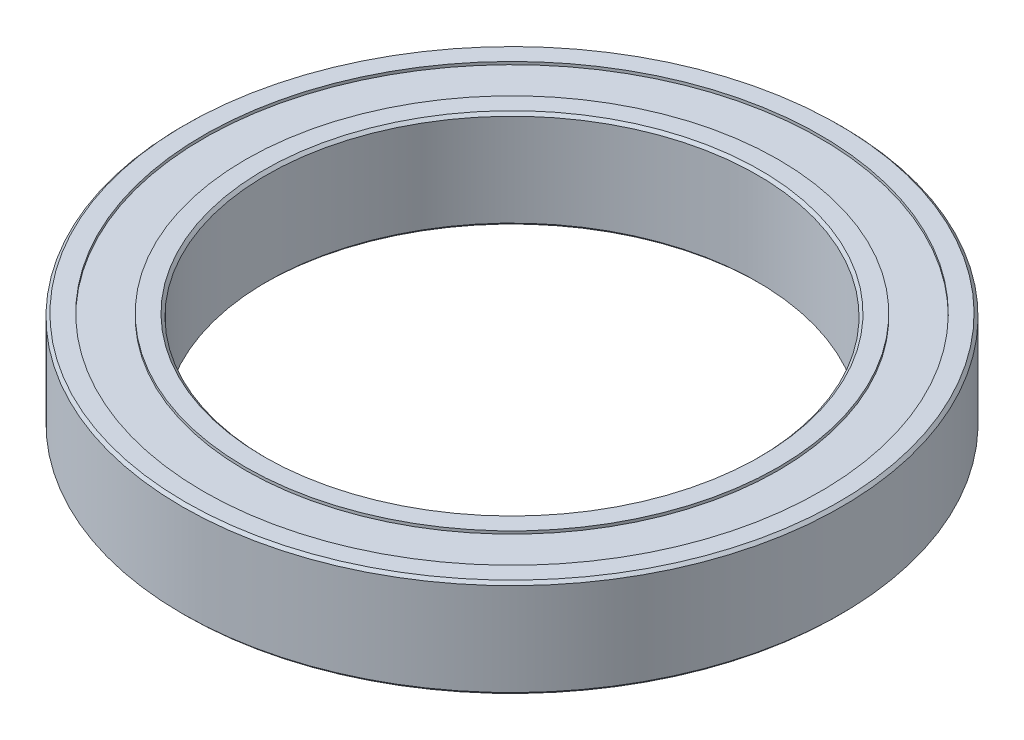
SolidWorks part; units mm, degrees
ref_plane "Front Plane" through (0, 0, 0) normal (0, 0, 1) x (1, 0, 0)
ref_plane "Top Plane" through (0, 0, 0) normal (0, 1, 0) x (1, 0, 0)
ref_plane "Right Plane" through (0, 0, 0) normal (1, 0, 0) x (0, 0, -1)
sketch "Sketch1" plane through (0, 0, 0) normal (0, 1, 0) x (1, 0, 0)
  circle A0 centre (0, 0) radius 23.5
  circle A1 centre (0, 0) radius 17.5
  dimension "D1" = 47
  dimension "D2" = 35
extrude "Boss-Extrude1" add sketch "Sketch1" along normal blind 7
sketch "Sketch2" plane through (0, 7, 0) normal (0, 1, 0) x (1, 0, 0)
  circle A0 centre (0, 0) radius 19
  circle A1 centre (0, 0) radius 22
  dimension "D1" = 44
  dimension "D2" = 38
extrude "Cut-Extrude1" cut sketch "Sketch2" against normal blind 0.2
sketch "Sketch3" plane through (0, 0, 0) normal (0, -1, 0) x (1, 0, 0)
  circle A0 centre (0, 0) radius 19 construction
  circle A1 centre (0, 0) radius 22
  circle A2 centre (0, 0) radius 22
  circle A3 centre (0, 0) radius 19
  dimension "D1" = 0
extrude "Cut-Extrude2" cut sketch "Sketch3" against normal blind 0.2
chamfer "Chamfer1" distance 0.2 angle 45 4 edges at (0, 7, 23.5) (0, 0, 23.5) (0, 7, 17.5) (0, 0, 17.5)
